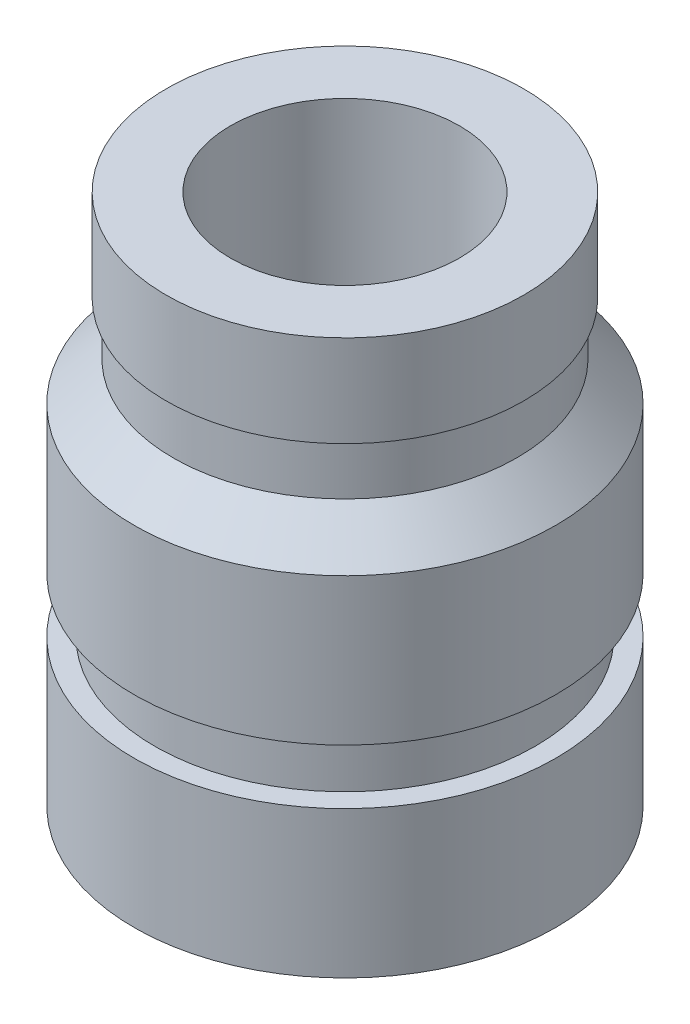
SolidWorks part; units mm, degrees
material "Brass"
ref_plane "Front Plane" through (0, 0, 0) normal (0, 0, 1) x (1, 0, 0)
ref_plane "Top Plane" through (0, 0, 0) normal (0, 1, 0) x (1, 0, 0)
ref_plane "Right Plane" through (0, 0, 0) normal (1, 0, 0) x (0, 0, -1)
sketch "Sketch1" plane through (0, 0, 0) normal (0, 0, 1) x (1, 0, 0)
  line L0 (0, -65.6336) -> (0, 3216.0474) construction
  line L1 (0, 0) -> (-2.3, 0)
  line L2 (-2.3, 0) -> (-2.3, 1.6)
  line L3 (-2.3, 1.6) -> (-2.075, 1.6)
  line L4 (-2.075, 1.6) -> (-2.075, 2.2)
  line L5 (-2.075, 2.2) -> (-2.3, 2.2)
  line L6 (-2.3, 2.2) -> (-2.3, 3.8)
  line L9 (-1.875, 4.8) -> (-1.95, 4.8)
  line L10 (-1.95, 4.8) -> (-1.95, 5.8)
  line L11 (-1.95, 5.8) -> (0, 5.8)
  line L12 (0, 5.8) -> (0, 0)
  line L13 (-2.3, 3.8) -> (-1.875, 4.225)
  line L14 (-1.875, 4.225) -> (-1.875, 4.8)
  line L15 (-2.3, 3.8) -> (0, 3.8) construction
  dimension "D1" = 4.6
  dimension "D2" = 5.8
  dimension "D3" = 1.6
  dimension "D4" = 1.6
  dimension "D5" = 45
  dimension "D6" = 4.15
  dimension "D7" = 1
  dimension "D8" = 3.75
  dimension "D9" = 3.9
  dimension "D10" = 0.6
revolve "Revolve1" add sketch "Sketch1" angle 360 about L0
sketch "Sketch2" plane through (0, 5.8, 0) normal (0, 1, 0) x (1, 0, 0)
  circle A0 centre (0, 0) radius 1.25
  dimension "D1" = 2.5
extrude "Cut-Extrude1" cut sketch "Sketch2" against normal through all
